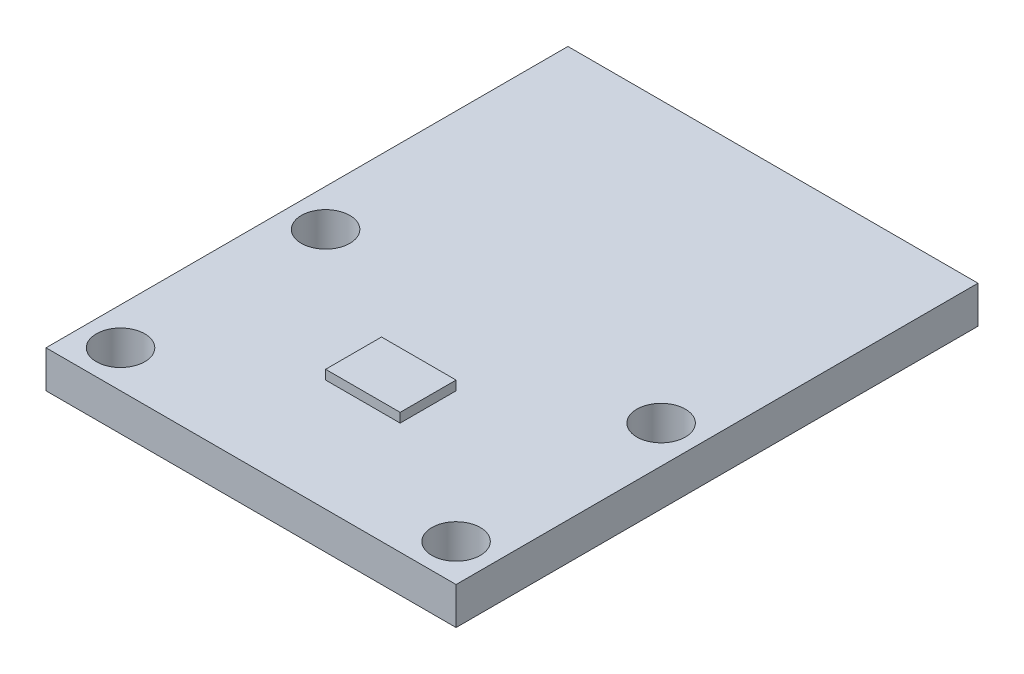
SolidWorks part; units mm, degrees
ref_plane "前视基准面" through (0, 0, 0) normal (0, 0, 1) x (1, 0, 0)
ref_plane "上视基准面" through (0, 0, 0) normal (0, 1, 0) x (1, 0, 0)
ref_plane "右视基准面" through (0, 0, 0) normal (1, 0, 0) x (0, 0, -1)
sketch "Sketch1" plane through (0, 0, 0) normal (0, 1, 0) x (1, 0, 0)
  line L0 (0, 16.8162) -> (0, -19.0399) construction
  line L1 (-11, 14) -> (11, 14)
  line L2 (-11, 14) -> (-11, -14)
  line L3 (-11, -14) -> (11, -14)
  line L4 (11, 14) -> (11, -14)
  circle A0 centre (9, -12) radius 1.3
  circle A1 centre (-9, -12) radius 1.3
  circle A2 centre (9, -1) radius 1.3
  circle A3 centre (-9, -1) radius 1.3
  point P0 (0, 0)
  dimension "D3" = 2.6
  dimension "D4" = 2.6
  dimension "D9" = 11
  dimension "D1" = 22
  dimension "D2" = 28
  dimension "D5" = 9
  dimension "D6" = 9
  dimension "D7" = 2
  dimension "D8" = 2
  dimension "D10" = 11
extrude "Boss-Extrude1" add sketch "Sketch1" along normal blind 2
sketch "Sketch2" plane through (0, 2, 0) normal (0, 1, 0) x (1, 0, 0)
  line L0 (0, 3.1918) -> (0, -15.2172) construction
  line L1 (9, -1) -> (9, -12) construction
  line L2 (11, -6.5) -> (-11, -6.5) construction
  line L3 (11, -14) -> (11, 14) construction
  line L4 (-11, 14) -> (-11, -14) construction
  line L6 (-2, -5) -> (2, -5)
  line L7 (-2, -5) -> (-2, -8)
  line L8 (-2, -8) -> (2, -8)
  line L9 (2, -5) -> (2, -8)
  line L10 (-2, -5) -> (2, -8) construction
  line L11 (-2, -8) -> (2, -5) construction
  point P13 (0, -6.5)
  dimension "D1" = 4
  dimension "D2" = 3
extrude "Boss-Extrude2" add sketch "Sketch2" along normal blind 0.5
